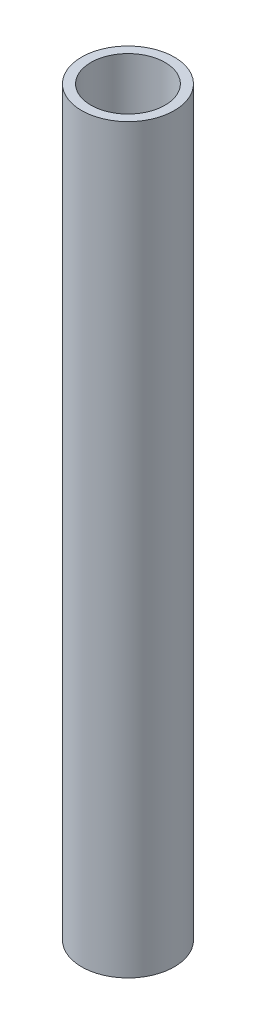
SolidWorks part; units mm, degrees
ref_plane "Front Plane" through (0, 0, 0) normal (0, 0, 1) x (1, 0, 0)
ref_plane "Top Plane" through (0, 0, 0) normal (0, 1, 0) x (1, 0, 0)
ref_plane "Right Plane" through (0, 0, 0) normal (1, 0, 0) x (0, 0, -1)
sketch "Sketch1" plane through (0, 0, 0) normal (0, 0, 1) x (1, 0, 0)
  line L0 (0, 0) -> (12.5, 0)
  line L1 (12.5, 0) -> (12.5, 200)
  line L3 (0, 200) -> (0, 0)
  line L4 (0, 200) -> (12.5, 200)
  dimension "D1" = 200
  dimension "D2" = 12.5
revolve "Revolve1" add sketch "Sketch1" angle 360 about L3
sketch "Sketch2" plane through (0, 200, 0) normal (0, 1, 0) x (1, 0, 0)
  circle A0 centre (0, 0) radius 10
  dimension "D1" = 20
extrude "Cut-Extrude1" cut sketch "Sketch2" against normal blind 71.5
